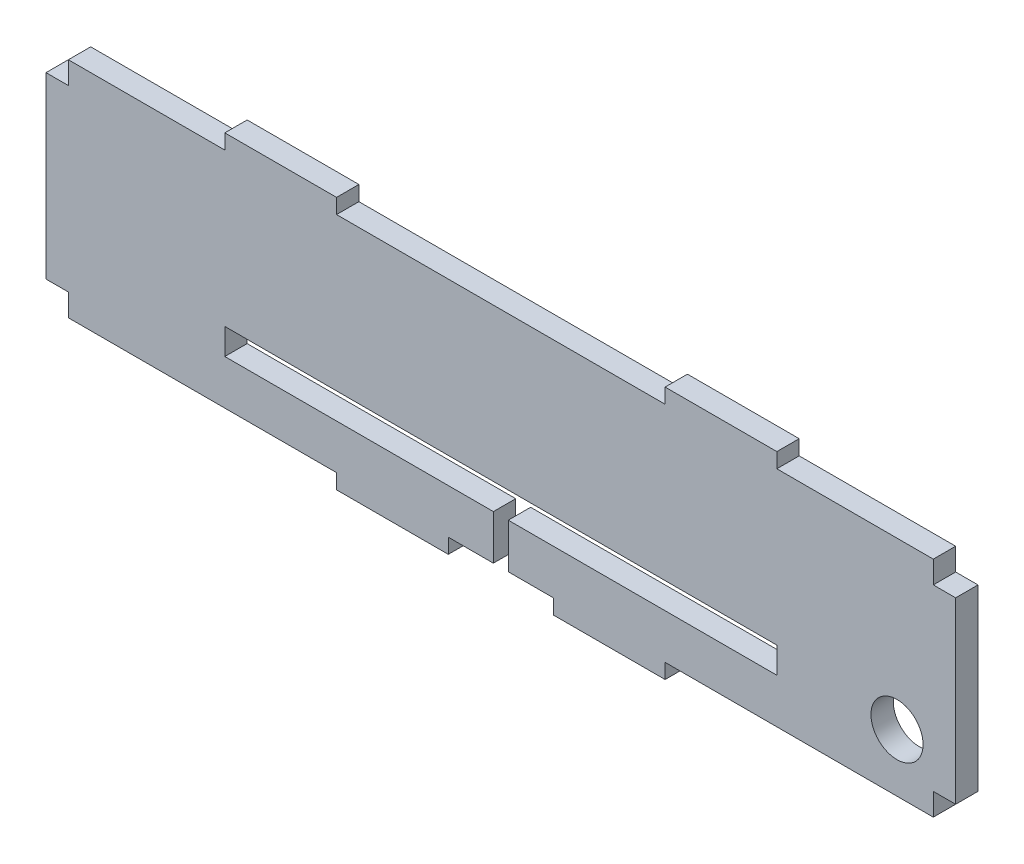
SolidWorks part; units mm, degrees
ref_plane "Front Plane" through (0, 0, 0) normal (0, 0, 1) x (1, 0, 0)
ref_plane "Top Plane" through (0, 0, 0) normal (0, 1, 0) x (1, 0, 0)
ref_plane "Right Plane" through (0, 0, 0) normal (1, 0, 0) x (0, 0, -1)
sketch "Sketch1" plane through (0, 0, 0) normal (0, 0, 1) x (1, 0, 0)
  line L0 (0, 0) -> (0, 43717.3993) construction
  line L1 (-5.9695, 0) -> (43711.4297, 0) construction
  line L2 (3, 0) -> (42, 0)
  line L4 (3, 0) -> (3, 30)
  line L6 (125.1, 0) -> (125.1, 30)
  line L7 (42, 0) -> (42, -2)
  line L8 (42, -2) -> (57, -2)
  line L9 (57, -2) -> (57, 0)
  line L10 (57, 0) -> (71.1, 0)
  line L11 (71.1, 0) -> (71.1, -2)
  line L12 (71.1, -2) -> (86.1, -2)
  line L13 (86.1, -2) -> (86.1, 0)
  line L14 (86.1, 0) -> (125.1, 0)
  line L15 (64.05, 0) -> (64.05, -50000) construction
  line L16 (27, 9.5) -> (101.1, 9.5)
  line L17 (27, 9.5) -> (27, 6)
  line L19 (101.1, 9.5) -> (101.1, 6)
  line L20 (65.05, 0) -> (65.05, 6)
  line L21 (63.05, 0) -> (65.05, 0)
  line L22 (63.05, 0) -> (63.05, 6)
  line L25 (27, 6) -> (63.05, 6)
  line L26 (65.05, 6) -> (101.1, 6)
  line L27 (3, 30) -> (27, 30)
  line L29 (42, 30) -> (42, 32)
  line L30 (42, 32) -> (27, 32)
  line L31 (27, 30) -> (27, 32)
  line L32 (42, 30) -> (86.1, 30)
  line L33 (125.1, 30) -> (101.1, 30)
  line L34 (101.1, 30) -> (101.1, 32)
  line L35 (86.1, 32) -> (101.1, 32)
  line L36 (86.1, 30) -> (86.1, 32)
  line L37 (125.1, 3) -> (122.1, 3)
  line L38 (3, 0) -> (6, 0)
  line L39 (3, 0) -> (3, 3)
  line L40 (3, 3) -> (6, 3)
  line L41 (6, 0) -> (6, 3)
  line L42 (122.1, 0) -> (122.1, 3)
  line L43 (125.1, 0) -> (122.1, 0)
  line L44 (125.1, 0) -> (125.1, 3)
  line L45 (-14.82, 15) -> (49985.18, 15) construction
  line L46 (125.1, 30) -> (122.1, 30)
  line L47 (122.1, 30) -> (122.1, 27)
  line L48 (125.1, 27) -> (122.1, 27)
  line L49 (125.1, 30) -> (125.1, 27)
  line L50 (3, 27) -> (6, 27)
  line L51 (6, 30) -> (6, 27)
  line L52 (3, 30) -> (6, 30)
  line L53 (3, 30) -> (3, 27)
  circle A0 centre (117.2288, 7.75) radius 3.5
  point P36 (64.05, 30)
  dimension "D15" = 7.75
  dimension "D1" = 122.1
  dimension "D2" = 30
  dimension "D3" = 15
  dimension "D4" = 15
  dimension "D5" = 14.1
  dimension "D6" = 15
  dimension "D7" = 2
  dimension "D8" = 2
  dimension "D9" = 15
  dimension "D10" = 15
  dimension "D11" = 6
  dimension "D12" = 3.5
  dimension "D13" = 15
  dimension "D14" = 2
  dimension "D16" = 15
extrude "Boss-Extrude3" add sketch "Sketch1" along normal blind 3 contours L36 L32 L29 L30 L31 L27 L4 L2 L7 L8 L9 L10 L22 L25 L17 L16 L19 L26 L20 L11 L12 L13 L14 L6 L33 L34 L35
